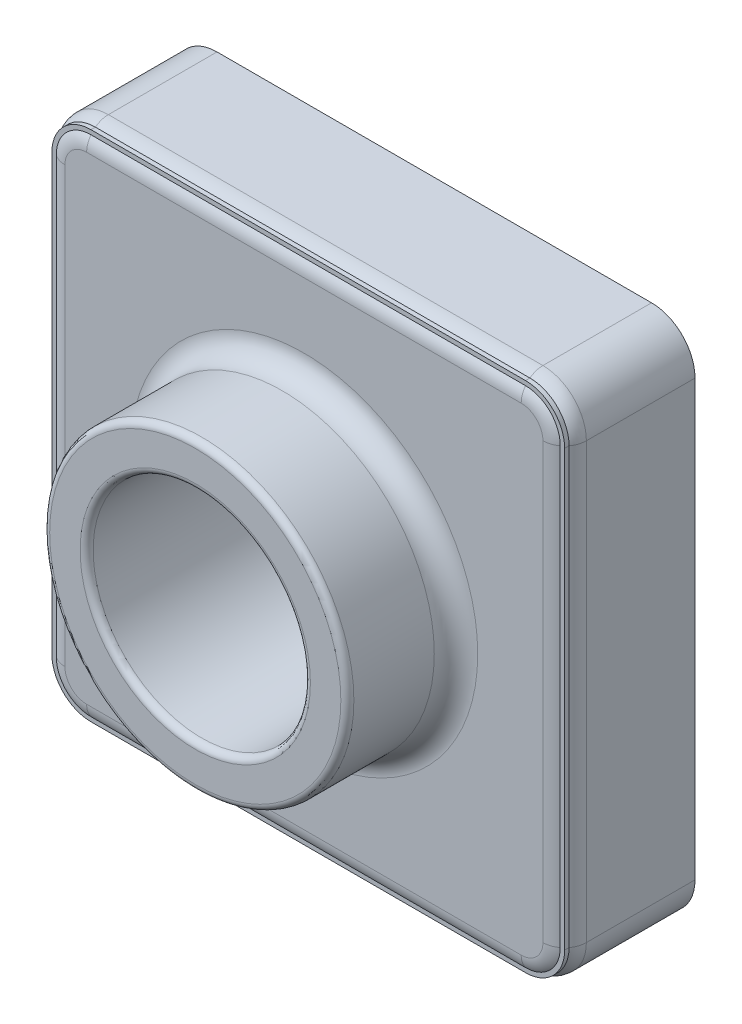
SolidWorks part; units mm, degrees
ref_plane "Front Plane" through (0, 0, 0) normal (0, 0, 1) x (1, 0, 0)
ref_plane "Top Plane" through (0, 0, 0) normal (0, 1, 0) x (1, 0, 0)
ref_plane "Right Plane" through (0, 0, 0) normal (1, 0, 0) x (0, 0, -1)
sketch "Sketch1" plane through (0, 0, 0) normal (0, 0, 1) x (1, 0, 0)
  line L1 (-60, 60) -> (60, 60)
  line L2 (-60, 60) -> (-60, -60)
  line L3 (-60, -60) -> (60, -60)
  line L4 (60, 60) -> (60, -60)
  line L5 (-60, 60) -> (60, -60) construction
  line L6 (-60, -60) -> (60, 60) construction
  point P1 (0, 0)
  dimension "D1" = 120
  dimension "D2" = 120
extrude "Boss-Extrude1" add sketch "Sketch1" against normal blind 30
sketch "Sketch2" plane through (0, 0, 0) normal (0, 0, 1) x (1, 0, 0)
  circle A0 centre (0, 0) radius 35
  dimension "D1" = 70
extrude "Boss-Extrude2" add sketch "Sketch2" along normal blind 25
ref_plane "Plane1" through (60, 60, 0) normal (0, 0, 1) x (1, 0, 0)
fillet "Fillet1" radius 10 1 edges at (60, 60, -15)
fillet "Fillet2" radius 10 1 edges at (-60, 60, -15)
fillet "Fillet3" radius 10 2 edges at (-60, -60, -15) (60, -60, -15)
fillet "Fillet4" radius 5 1 edges at (35, 0, 0)
sketch "Sketch9" plane through (0, 0, 25) normal (0, 0, 1) x (1, 0, 0)
  circle A0 centre (0, 0) radius 25
  dimension "D1" = 50
extrude "Cut-Extrude1" cut sketch "Sketch9" against normal through all
fillet "Fillet5" radius 1.5 2 edges at (35, 0, 25) (25, 0, 25)
shell "Shell1" thickness 1
fillet "Fillet6" radius 5 8 edges at (-57.0711, 57.0711, 0) (0, 60, 0) (57.0711, 57.0711, 0) (60, 0, 0) (57.0711, -57.0711, 0) (0, -60, 0) (-57.0711, -57.0711, 0) (-60, 0, 0)
